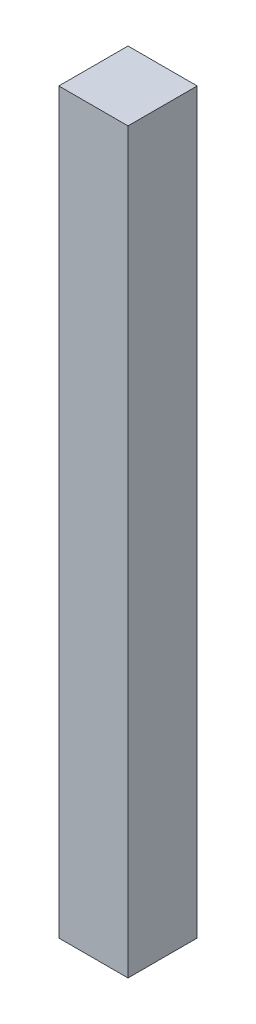
SolidWorks part; units mm, degrees
material "Pine"
ref_plane "Front Plane" through (0, 0, 0) normal (0, 0, 1) x (1, 0, 0)
ref_plane "Top Plane" through (0, 0, 0) normal (0, 1, 0) x (1, 0, 0)
ref_plane "Right Plane" through (0, 0, 0) normal (1, 0, 0) x (0, 0, -1)
sketch "Sketch1" plane through (0, 0, 0) normal (0, 0, 1) x (1, 0, 0)
  line L1 (0, 0) -> (19.05, 0)
  line L2 (0, 0) -> (0, 203.2)
  line L3 (0, 203.2) -> (19.05, 203.2)
  line L4 (19.05, 0) -> (19.05, 203.2)
  dimension "D1" = 19.05
  dimension "D2" = 203.2
extrude "Boss-Extrude1" add sketch "Sketch1" along normal blind 19.05
